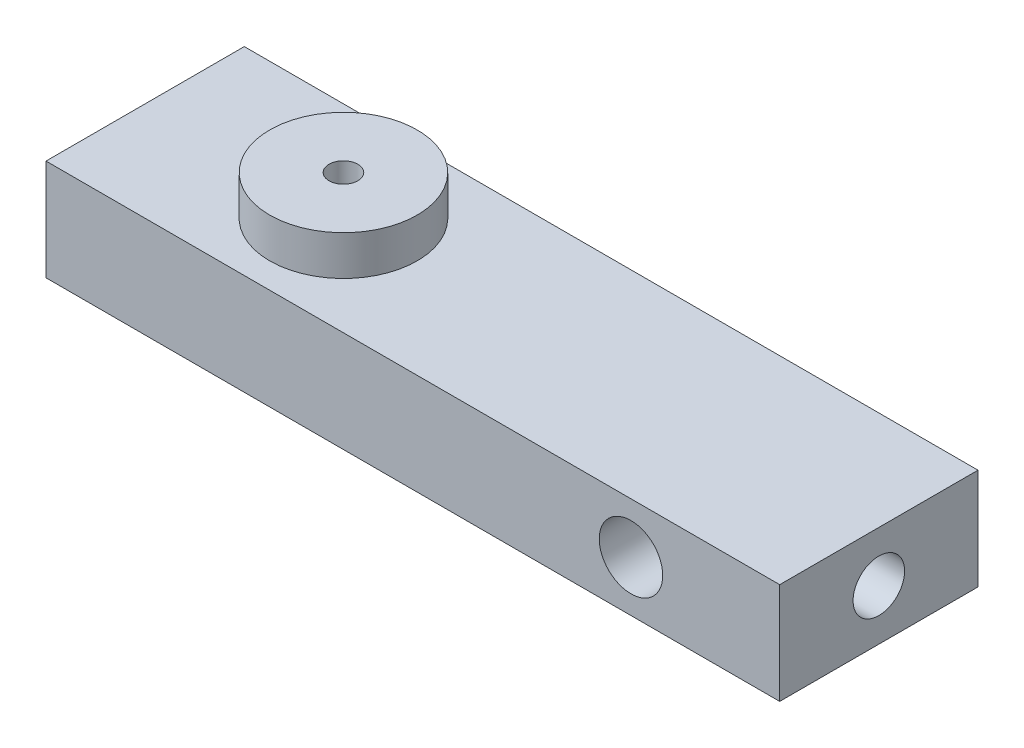
SolidWorks part; units mm, degrees
ref_plane "前视基准面" through (0, 0, 0) normal (0, 0, 1) x (1, 0, 0)
ref_plane "上视基准面" through (0, 0, 0) normal (0, 1, 0) x (1, 0, 0)
ref_plane "右视基准面" through (0, 0, 0) normal (1, 0, 0) x (0, 0, -1)
other "Configuration Table"
sketch "草图1" plane through (0, 0, 0) normal (0, 1, 0) x (1, 0, 0)
  line L1 (-7.5, 5) -> (7.5, 5)
  line L2 (-7.5, 5) -> (-7.5, -5)
  line L3 (-7.5, -5) -> (7.5, -5)
  line L4 (7.5, 5) -> (7.5, -5)
  line L5 (-7.5, 5) -> (7.5, -5) construction
  line L6 (-7.5, -5) -> (7.5, 5) construction
  point P0 (0, 0)
  dimension "D1" = 15
  dimension "D2" = 10
extrude "凸台-拉伸1" add sketch "草图1" along normal blind 5.1
sketch "草图2" plane through (0, 0, 5) normal (0, 0, 1) x (1, 0, 0)
  circle A0 centre (0, 2.55) radius 1.6
  point P2 (0, 0)
  dimension "D1" = 3.2
  dimension "D2" = 2.55
extrude "切除-拉伸1" cut sketch "草图2" against normal through all
sketch "草图3" plane through (7.5, 0, 0) normal (1, 0, 0) x (0, 0, -1)
  line L3 (-2.5032, 2.55) -> (3.0272, 2.55) construction
  line L4 (-5, 5.1) -> (5, 5.1) construction
  line L5 (-5, 0) -> (5, 0) construction
  circle A0 centre (0, 2.55) radius 1.3
  dimension "D1" = 2.6
extrude "切除-拉伸2" cut sketch "草图3" against normal blind 3.8
sketch "草图4" plane through (3.7, 0, 0) normal (1, 0, 0) x (0, 0, -1)
  circle A0 centre (0, 2.55) radius 0.575
  dimension "D1" = 1.15
extrude "切除-拉伸3" cut sketch "草图4" against normal up to next
sketch "草图5" plane through (-7.5, 0, 0) normal (-1, 0, 0) x (0, 0, 1)
  line L4 (-5, 0) -> (5, 0)
  line L5 (5, 0) -> (5, 5.1)
  line L6 (5, 5.1) -> (-5, 5.1)
  line L7 (-5, 5.1) -> (-5, 0)
  line L8 (-5, 0) -> (5, 0)
  line L9 (5, 0) -> (5, 5.1)
  line L10 (5, 5.1) -> (-5, 5.1)
  line L11 (-5, 5.1) -> (-5, 0)
  dimension "D1" = 0
extrude "凸台-拉伸2" add sketch "草图5" along normal blind 22
sketch "草图6" plane through (0, 5.1, 0) normal (0, 1, 0) x (1, 0, 0)
  line L0 (-29.5, -5) -> (-29.5, 5) construction
  circle A0 centre (-19.5, 0) radius 3.72
  dimension "D2" = 7.44
  dimension "D1" = 10
extrude "凸台-拉伸3" add sketch "草图6" along normal blind 2
sketch "草图7" plane through (0, 7.1, 0) normal (0, 1, 0) x (1, 0, 0)
  circle A0 centre (-19.5, 0) radius 0.725
  circle A1 centre (-19.5, 0) radius 3.72 construction
  dimension "D1" = 1.45
extrude "切除-拉伸4" cut sketch "草图7" against normal through all
